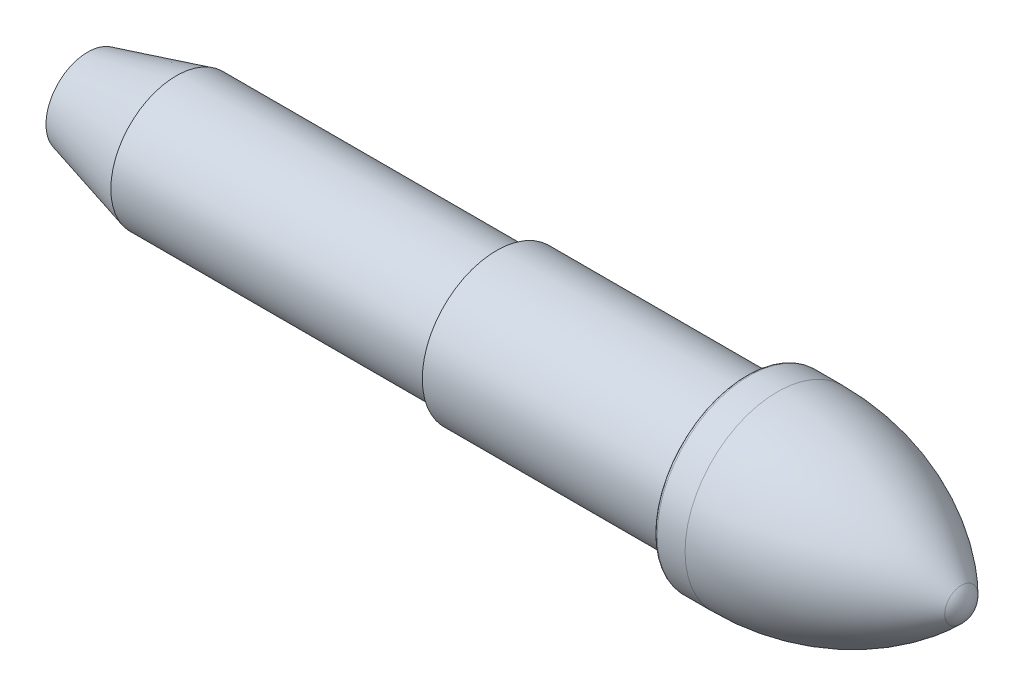
SolidWorks part; units mm, degrees
ref_plane "Frontal" through (0, 0, 0) normal (0, 0, 1) x (1, 0, 0)
ref_plane "Superior" through (0, 0, 0) normal (0, 1, 0) x (1, 0, 0)
ref_plane "Lateral" through (0, 0, 0) normal (1, 0, 0) x (0, 0, -1)
sketch "Sketch1" plane through (0, 0, 0) normal (0, 0, 1) x (1, 0, 0)
  line L0 (0, 0) -> (34.7806, 0) construction
  line L1 (0, 0) -> (0, 1.335)
  line L2 (0, 1.335) -> (2.8364, 2.095)
  line L3 (2.8364, 2.095) -> (13.09, 2.095)
  line L4 (13.09, 2.095) -> (13.09, 2.375)
  line L5 (13.09, 2.375) -> (21.09, 2.375)
  line L6 (21.09, 2.375) -> (21.09, 2.955)
  line L7 (0, 0) -> (28.2, 0)
  line L9 (21.09, 2.955) -> (22.0847, 2.955)
  arc A0 (22.0847, 2.955) -> (27.9774, 0.5333) centre (22.0847, -5.425) cw
  arc A1 (27.9774, 0.5333) -> (28.2, 0) centre (27.45, 0) cw
  dimension "D9" = 8.38
  dimension "D5" = 0.75
  dimension "D12" = 5.425
  dimension "D13" = 6.1153
  dimension "D18" = 0.9947
  dimension "D2" = 2.8364
  dimension "D3" = 10.2536
  dimension "D4" = 8
  dimension "D6" = 4.19
  dimension "D7" = 4.75
  dimension "D8" = 5.91
  dimension "D10" = 15
  dimension "D11" = 0.9947
  dimension "D14" = 7.11
  dimension "D15" = 28.2
  dimension "D16" = 21.09
  dimension "D17" = 2.67
revolve "Base-Revolve" add sketch "Sketch1" angle 360 about L0
fillet "Fillet1" radius 0.1 1 edges at (21.09, 0, 2.955)
ref_plane "Plano1" through (28.2, 0, 0) normal (1, 0, 0) x (0, 0, -1)
